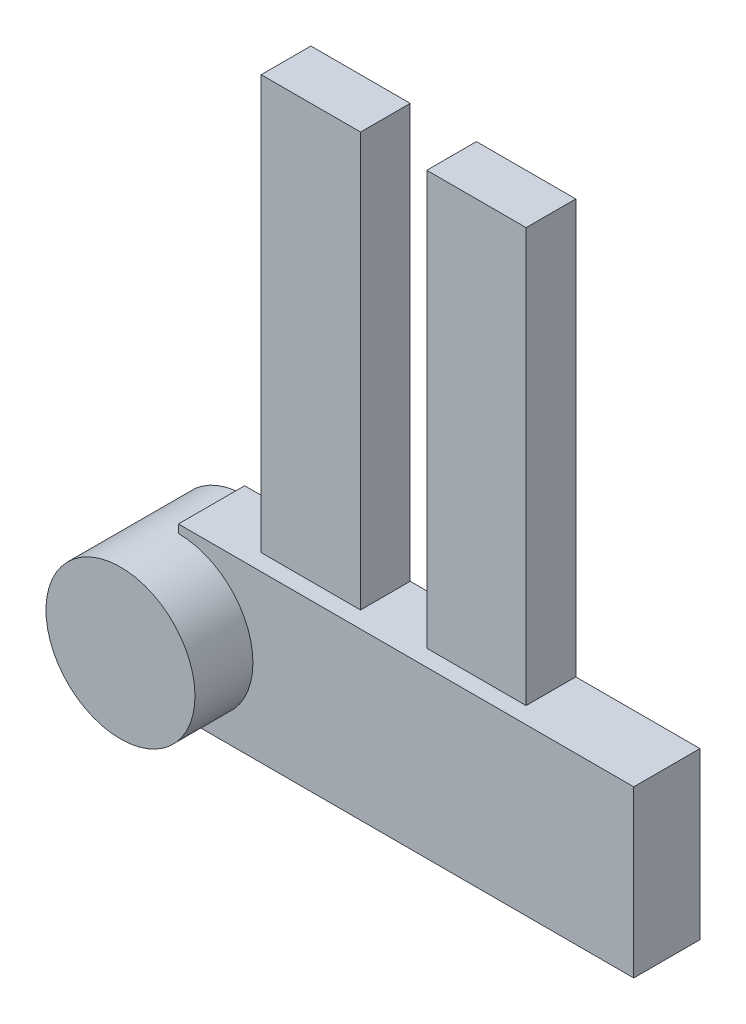
SolidWorks part; units mm, degrees
ref_plane "前视基准面" through (0, 0, 0) normal (0, 0, 1) x (1, 0, 0)
ref_plane "上视基准面" through (0, 0, 0) normal (0, 1, 0) x (1, 0, 0)
ref_plane "右视基准面" through (0, 0, 0) normal (1, 0, 0) x (0, 0, -1)
other "Configuration Table"
sketch "草图1" plane through (0, 0, 0) normal (0, 0, 1) x (1, 0, 0)
  line L1 (230000, 105000) -> (285000, 105000)
  line L2 (230000, 105000) -> (230000, 125000)
  line L3 (230000, 125000) -> (285000, 125000)
  line L4 (285000, 105000) -> (285000, 125000)
extrude "凸台-拉伸1" add sketch "草图1" along normal blind 8000
sketch "草图2" plane through (0, 0, 0) normal (0, 0, 1) x (1, 0, 0)
  line L0 (230000, 125000) -> (230000, 105000) construction
  circle A0 centre (230000, 115000) radius 9000
extrude "凸台-拉伸2" add sketch "草图2" along normal blind 15000
sketch "草图3" plane through (0, 0, 0) normal (0, 0, 1) x (1, 0, 0)
  line L1 (238000, 123000) -> (250000, 123000)
  line L2 (238000, 123000) -> (238000, 175000)
  line L3 (238000, 175000) -> (250000, 175000)
  line L4 (250000, 123000) -> (250000, 175000)
extrude "凸台-拉伸3" add sketch "草图3" along normal blind 6000
sketch "草图4" plane through (0, 0, 0) normal (0, 0, 1) x (1, 0, 0)
  line L1 (258000, 123000) -> (270000, 123000)
  line L2 (258000, 123000) -> (258000, 175000)
  line L3 (258000, 175000) -> (270000, 175000)
  line L4 (270000, 123000) -> (270000, 175000)
extrude "凸台-拉伸4" add sketch "草图4" along normal blind 6000
